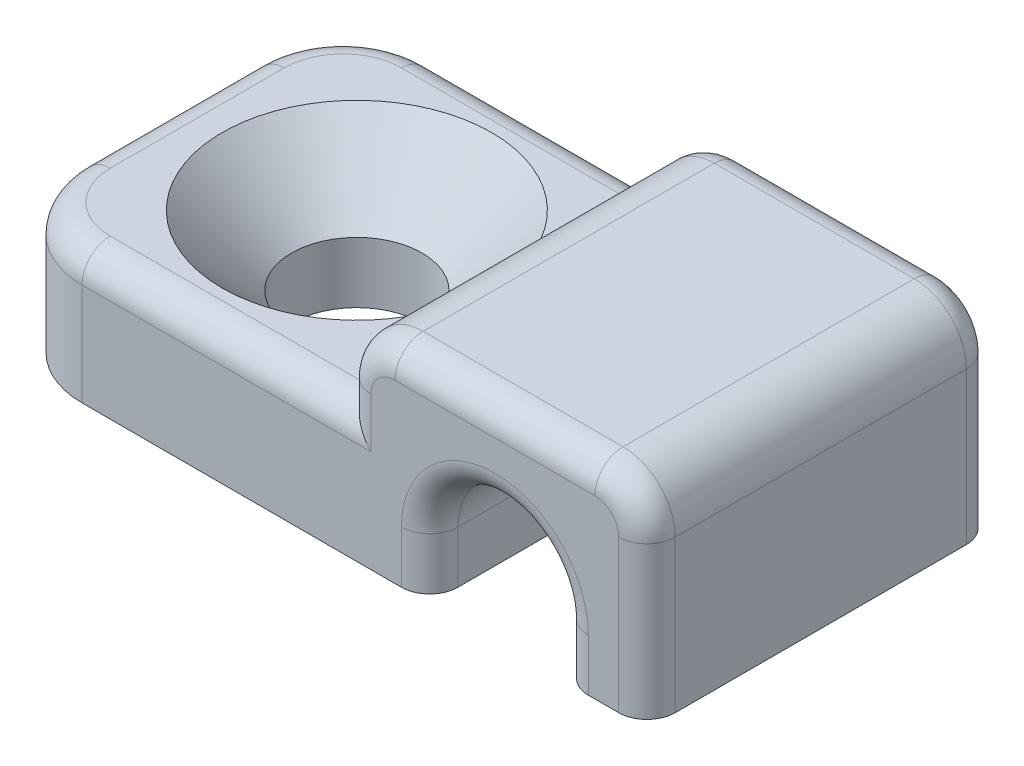
SolidWorks part; units mm, degrees
ref_plane "Plano frontal" through (0, 0, 0) normal (0, 0, 1) x (1, 0, 0)
ref_plane "Plano superior" through (0, 0, 0) normal (0, 1, 0) x (1, 0, 0)
ref_plane "Plano direito" through (0, 0, 0) normal (1, 0, 0) x (0, 0, -1)
sketch "Esboço1" plane through (0, 0, 0) normal (0, 0, 1) x (1, 0, 0)
  line L1 (-11.5, -1.2) -> (-11.5, 1.8)
  line L2 (-11.5, 1.8) -> (-3.5, 1.8)
  line L3 (-3.5, 1.8) -> (-3.5, 3.5)
  line L4 (-3.5, 3.5) -> (3.5, 3.5)
  line L5 (3.5, 3.5) -> (3.5, -1.2)
  line L7 (-1.5, 0) -> (-1.5, -1.2)
  line L8 (1.5, 0) -> (1.5, -1.2)
  line L9 (-11.5, -1.2) -> (-1.5, -1.2)
  line L11 (1.5, -1.2) -> (3.5, -1.2)
  arc A0 (1.5, 0) -> (-1.5, 0) centre (0, 0) ccw
  circle A1 centre (0, 0) radius 1.5 construction
  dimension "D1" = 3
  dimension "D7" = 3
  dimension "D2" = 1.2
  dimension "D3" = 8
  dimension "D4" = 3.5
  dimension "D5" = 3.5
  dimension "D6" = 3.5
  dimension "D8" = 3
extrude "Ressalto-extrusão1" add sketch "Esboço1" along normal blind 8
sketch "Esboço2" plane through (0, 1.8, 0) normal (0, 1, 0) x (1, 0, 0)
  line L0 (-3.5, -7.35) -> (-10.85, -0.65) construction
  circle A0 centre (-7.175, -4) radius 1.5
  point P6 (-3, -8)
  point P7 (-3, -7.5)
  point P9 (0, 0)
  point P10 (-10.5, -0.5)
  point P11 (0, 0)
  point P15 (0, 0)
  dimension "D1" = 3
extrude "Corte-extrusão1" cut sketch "Esboço2" against normal blind 6
chamfer "Chanfro2" distance 1.6 angle 45 1 edges at (-8.675, 1.8, 4)
fillet "Filete3" radius 2 2 edges at (-11.5, 0.3, 8) (-11.5, 0.3, 0)
fillet "Filete5" radius 1.2 2 edges at (-3.5, 3.5, 4) (3.5, 3.5, 4)
fillet "Filete6" radius 0.65 21 edges at (-1.5, -0.6, 8) (1.5, -0.6, 8) (-1.5, -0.6, 0) (1.5, -0.6, 0) (3.5, 0.55, 8) (3.1485, 3.1485, 8) (-3.5, 2.05, 8) (-3.1485, 3.1485, 8) (-6.5, 1.8, 8) (-10.9142, 1.8, 7.4142) (-6.5, 1.8, 0) (-10.9142, 1.8, 0.5858) (3.5, 0.55, 0) (3.1485, 3.1485, 0) (-3.5, 2.05, 0) (-3.1485, 3.1485, 0) (0, 1.5, 8) (0, 1.5, 0) (0, 3.5, 8) (-11.5, 1.8, 4) (0, 3.5, 0)
